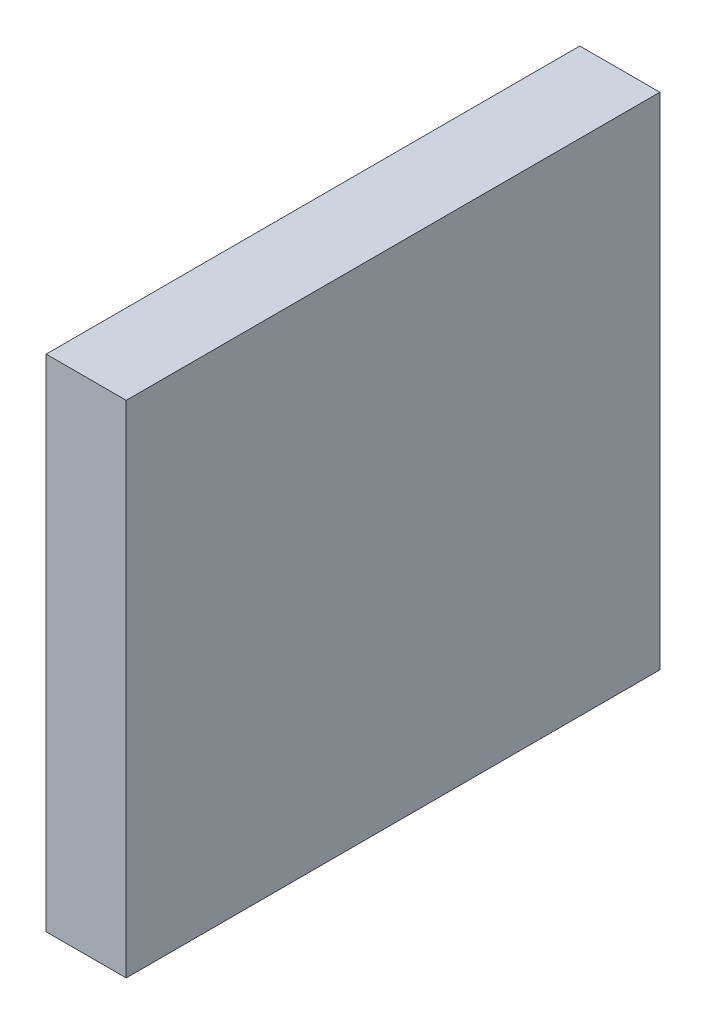
SolidWorks part; units mm, degrees
ref_plane "Front Plane" through (0, 0, 0) normal (0, 0, 1) x (1, 0, 0)
ref_plane "Top Plane" through (0, 0, 0) normal (0, 1, 0) x (1, 0, 0)
ref_plane "Right Plane" through (0, 0, 0) normal (1, 0, 0) x (0, 0, -1)
sketch "Sketch1" plane through (0, 0, 0) normal (0, 0, 1) x (1, 0, 0)
  line L1 (0, 0) -> (14.4, 0)
  line L2 (0, 0) -> (0, 90)
  line L3 (0, 90) -> (14.4, 90)
  line L4 (14.4, 0) -> (14.4, 90)
  dimension "D1" = 14.4
  dimension "D2" = 90
extrude "Boss-Extrude1" add sketch "Sketch1" along normal blind 96
